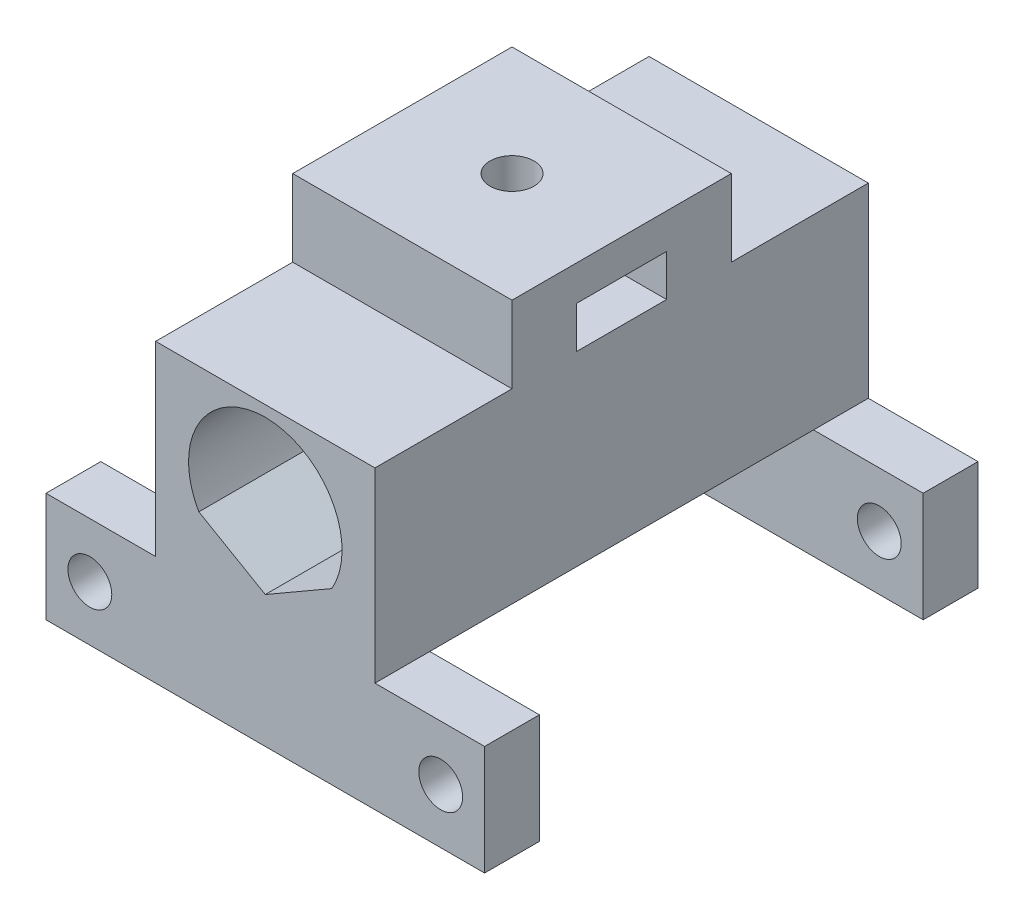
SolidWorks part; units mm, degrees
ref_plane "Front Plane" through (0, 0, 0) normal (0, 0, 1) x (1, 0, 0)
ref_plane "Top Plane" through (0, 0, 0) normal (0, 1, 0) x (1, 0, 0)
ref_plane "Right Plane" through (0, 0, 0) normal (1, 0, 0) x (0, 0, -1)
sketch "Sketch1" plane through (0, 0, 0) normal (0, 1, 0) x (1, 0, 0)
  line L1 (-10, -22.5) -> (10, -22.5)
  line L2 (-10, -22.5) -> (-10, 22.5)
  line L3 (-10, 22.5) -> (10, 22.5)
  line L4 (10, -22.5) -> (10, 22.5)
  line L5 (-10, -22.5) -> (10, 22.5) construction
  line L6 (-10, 22.5) -> (10, -22.5) construction
  point P0 (0, 0)
  dimension "D1" = 20
  dimension "D2" = 45
extrude "Boss-Extrude1" add sketch "Sketch1" along normal blind 17
sketch "Sketch2" plane through (0, 0, 22.5) normal (0, 0, 1) x (1, 0, 0)
  line L0 (0, 2) -> (-6.0622, 5.5)
  line L1 (-10, 0) -> (10, 0) construction
  line L2 (0, 2) -> (-6.4072, 2) construction
  line L3 (0, 17) -> (0, 16) construction
  line L4 (0, -9.35) -> (0, 9.35) construction
  line L5 (-10, 17) -> (10, 17) construction
  line L7 (0, 9) -> (0, 2) construction
  line L8 (0, 2) -> (6.0622, 5.5)
  arc A0 (6.0622, 5.5) -> (-6.0622, 5.5) centre (0, 9) ccw
  dimension "D1" = 2
  dimension "D2" = 3.5
  dimension "D3" = 30
extrude "Cut-Extrude1" cut sketch "Sketch2" against normal through all
sketch "Sketch3" plane through (0, 0, 22.5) normal (0, 0, 1) x (1, 0, 0)
  line L0 (10, 0) -> (20, 0)
  line L1 (20, 0) -> (20, -10)
  line L2 (20, -10) -> (-20, -10)
  line L3 (-20, -10) -> (-20, 0)
  line L4 (-20, 0) -> (-10, 0)
  line L5 (-10, 0) -> (10, 0)
  dimension "D1" = 10
  dimension "D2" = 10
  dimension "D3" = 10
extrude "Boss-Extrude2" add sketch "Sketch3" against normal blind 5
mirror "Mirror1" about plane through (0, 0, 0) normal (0, 0, 1) of "Boss-Extrude2"
sketch "Sketch4" plane through (0, 0, 22.5) normal (0, 0, 1) x (1, 0, 0)
  line L0 (20, -10) -> (20, 0) construction
  line L1 (20, 0) -> (10, 0) construction
  line L2 (0, -14.85) -> (0, 14.85) construction
  circle A0 centre (16, -5) radius 2
  circle A1 centre (-16, -5) radius 2
  dimension "D1" = 4
  dimension "D2" = 4
  dimension "D3" = 5
extrude "Cut-Extrude2" cut sketch "Sketch4" against normal through all
sketch "Sketch6" plane through (0, 17, 0) normal (0, 1, 0) x (1, 0, 0)
  line L0 (10, -22.5) -> (10, 22.5) construction
  line L1 (-10, -10) -> (10, -10)
  line L2 (-10, -10) -> (-10, 10)
  line L3 (-10, 10) -> (10, 10)
  line L4 (10, -10) -> (10, 10)
  line L5 (-10, -10) -> (10, 10) construction
  line L6 (-10, 10) -> (10, -10) construction
  point P0 (0, 0)
  dimension "D1" = 20
extrude "Boss-Extrude3" add sketch "Sketch6" along normal blind 7 contours L2 L1 L4 L3
sketch "Sketch8" plane through (10, 0, 0) normal (1, 0, 0) x (0, 0, -1)
  line L0 (10, 17) -> (22.5, 17) construction
  line L5 (-4.1, 17) -> (4.1, 17)
  line L6 (-4.1, 17) -> (-4.1, 20.8)
  line L7 (-4.1, 20.8) -> (4.1, 20.8)
  line L8 (4.1, 17) -> (4.1, 20.8)
  line L9 (-4.1, 17) -> (4.1, 20.8) construction
  line L10 (-4.1, 20.8) -> (4.1, 17) construction
  line L11 (-10, 24) -> (-10, 17) construction
  point P0 (0, 18.9)
  point P7 (0, 0)
  point P8 (0, 18.95)
  dimension "D1" = 8.2
  dimension "D2" = 3.8
  dimension "D3" = 5.9
extrude "Cut-Extrude3" cut sketch "Sketch8" against normal through all
sketch "Sketch7" plane through (0, 24, 0) normal (0, 1, 0) x (1, 0, 0)
  circle A0 centre (0, 0) radius 2
extrude "Cut-Extrude4" cut sketch "Sketch7" against normal up to next
